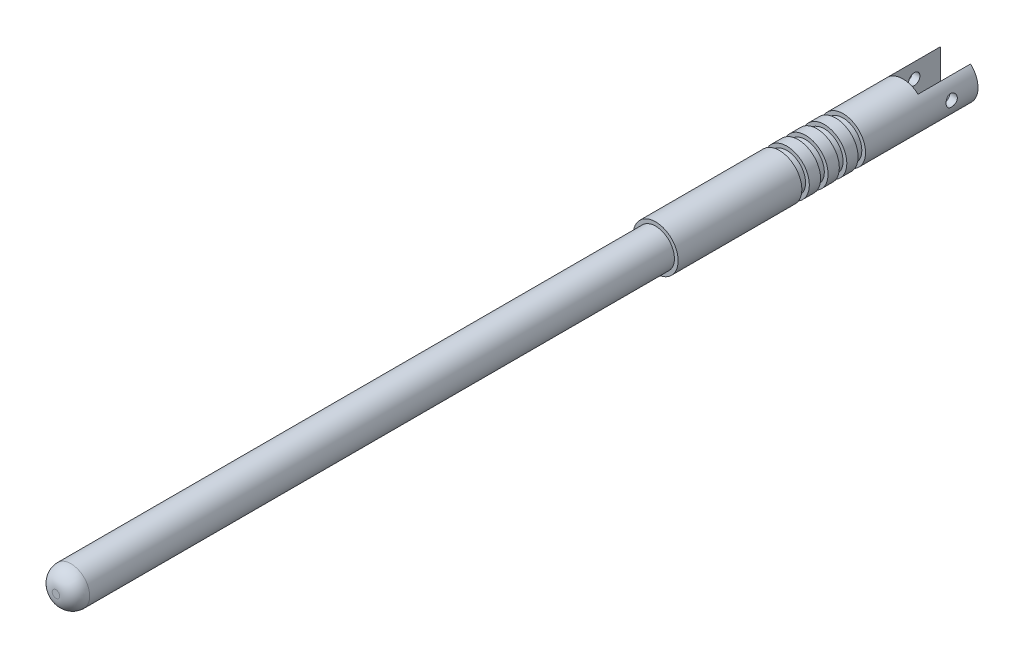
SolidWorks part; units mm, degrees
ref_plane "Front Plane" through (0, 0, 0) normal (0, 0, 1) x (1, 0, 0)
ref_plane "Top Plane" through (0, 0, 0) normal (0, 1, 0) x (1, 0, 0)
ref_plane "Right Plane" through (0, 0, 0) normal (1, 0, 0) x (0, 0, -1)
sketch "Sketch2" plane through (0, 0, 0) normal (0, 0, 1) x (1, 0, 0)
  circle A0 centre (0, 0) radius 3
extrude "Boss-Extrude1" add sketch "Sketch2" along normal blind 15
sketch "Sketch3" plane through (0, 0, 0) normal (0, 0, -1) x (-1, 0, 0)
  line L0 (2, 3.1832) -> (-2, 3.1832)
  line L4 (2, -2) -> (2, 3.1832)
  line L5 (-2, 3.1832) -> (-2, -2)
  line L6 (-2, -2) -> (2, -2)
extrude "Cut-Extrude1" cut sketch "Sketch3" against normal blind 7
sketch "Sketch4" plane through (-2, 0, 0) normal (1, 0, 0) x (0, 0, -1)
  circle A0 centre (-3.5, 0.2361) radius 0.75
extrude "Cut-Extrude4" cut sketch "Sketch4" along normal blind 6 and the other way blind 3
sketch "Sketch12" plane through (0, 0, 15) normal (0, 0, 1) x (1, 0, 0)
  circle A1 centre (0, 0) radius 2.5
extrude "Boss-Extrude2" add sketch "Sketch12" along normal blind 1
sketch "Sketch13" plane through (0, 0, 16) normal (0, 0, 1) x (1, 0, 0)
  circle A0 centre (0, 0) radius 3
extrude "Boss-Extrude3" add sketch "Sketch13" along normal blind 1.5
sketch "Sketch14" plane through (0, 0, 17.5) normal (0, 0, 1) x (1, 0, 0)
  circle A0 centre (0, 0) radius 2.5
extrude "Boss-Extrude4" add sketch "Sketch14" along normal blind 1
sketch "Sketch15" plane through (0, 0, 18.5) normal (0, 0, 1) x (1, 0, 0)
  circle A0 centre (0, 0) radius 3
extrude "Boss-Extrude5" add sketch "Sketch15" along normal blind 1.5
sketch "Sketch16" plane through (0, 0, 20) normal (0, 0, 1) x (1, 0, 0)
  circle A0 centre (0, 0) radius 2.5
extrude "Boss-Extrude6" add sketch "Sketch16" along normal blind 1
sketch "Sketch17" plane through (0, 0, 21) normal (0, 0, 1) x (1, 0, 0)
  circle A0 centre (0, 0) radius 3
extrude "Boss-Extrude7" add sketch "Sketch17" along normal blind 1.5
sketch "Sketch18" plane through (0, 0, 22.5) normal (0, 0, 1) x (1, 0, 0)
  circle A0 centre (0, 0) radius 2.5
extrude "Boss-Extrude8" add sketch "Sketch18" along normal blind 1
sketch "Sketch19" plane through (0, 0, 23.5) normal (0, 0, 1) x (1, 0, 0)
  circle A0 centre (0, 0) radius 3
extrude "Boss-Extrude9" add sketch "Sketch19" along normal blind 16.5
sketch "Sketch22" plane through (0, 0, 40) normal (0, 0, 1) x (1, 0, 0)
sketch "Sketch28" plane through (0, 0, 40) normal (0, 0, 1) x (1, 0, 0)
  circle A0 centre (0, 0) radius 2.5
extrude "Boss-Extrude11" add sketch "Sketch28" along normal blind 80
fillet "Fillet6" radius 2 1 edges at (2.5, 0, 120)
